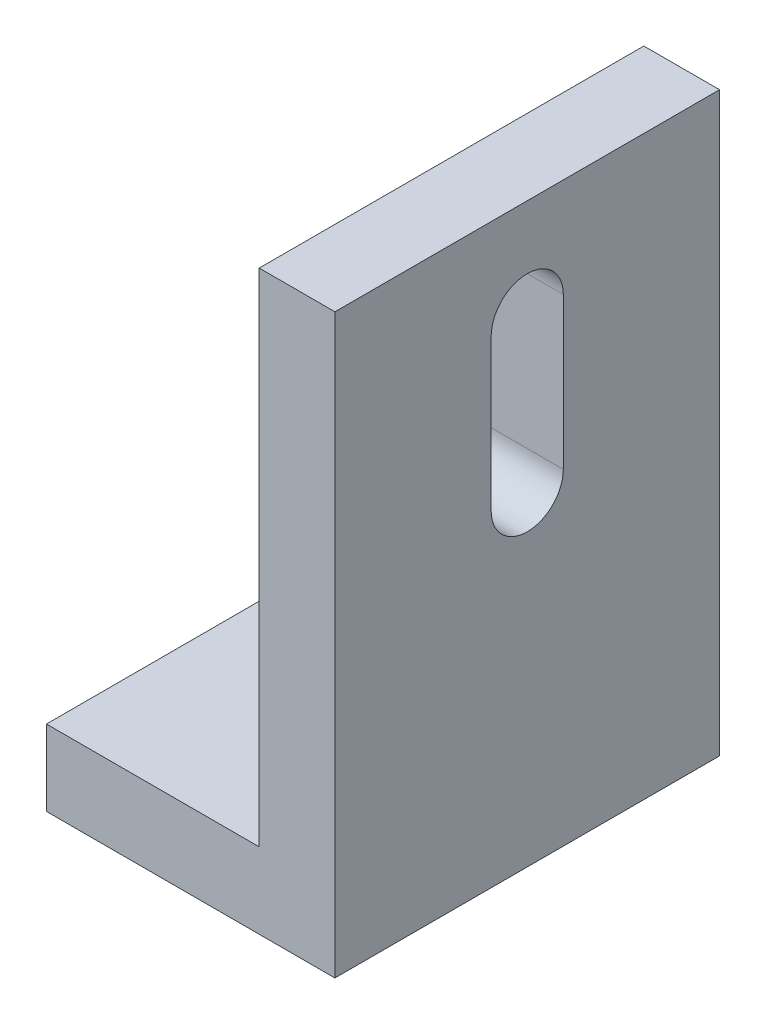
SolidWorks part; units mm, degrees
material "Aleación 6061"
ref_plane "Alzado" through (0, 0, 0) normal (0, 0, 1) x (1, 0, 0)
ref_plane "Planta" through (0, 0, 0) normal (0, 1, 0) x (1, 0, 0)
ref_plane "Vista lateral" through (0, 0, 0) normal (1, 0, 0) x (0, 0, -1)
sketch "Croquis1" plane through (0, 0, 0) normal (0, 0, 1) x (1, 0, 0)
  line L0 (0, 0) -> (38.1, 0)
  line L1 (38.1, 0) -> (38.1, 76.2)
  dimension "D1" = 76.2
  dimension "D2" = 38.1
extrude "Extruir-Lámina1" add sketch "Croquis1" along normal mid plane 50.8 thin thin type one direction reverse wall 10
sketch "Croquis2" plane through (0, 10, 0) normal (0, 1, 0) x (1, 0, 0)
  line L0 (14.05, 25.4) -> (14.05, -25.4) construction
  line L1 (0, 25.4) -> (28.1, 25.4) construction
  line L2 (0, -25.4) -> (28.1, -25.4) construction
  line L3 (0, 0) -> (28.1, 0) construction
  line L4 (28.1, -25.4) -> (28.1, 25.4) construction
  circle A0 centre (14.05, 0) radius 4.7625
  dimension "D1" = 9.525
extrude "Cortar-Extruir1" cut sketch "Croquis2" against normal through all
sketch "Croquis3" plane through (28.1, 0, 0) normal (-1, 0, 0) x (0, 0, 1)
  line L0 (0, 76.2) -> (0, 10) construction
  line L1 (25.4, 76.2) -> (-25.4, 76.2) construction
  line L2 (25.4, 10) -> (-25.4, 10) construction
  line L3 (0, 43.1) -> (0, 63.1) construction
  line L4 (-4.7625, 43.1) -> (-4.7625, 63.1)
  line L5 (4.7625, 43.1) -> (4.7625, 63.1)
  arc A0 (-4.7625, 43.1) -> (4.7625, 43.1) centre (0, 43.1) ccw
  arc A1 (4.7625, 63.1) -> (-4.7625, 63.1) centre (0, 63.1) ccw
  point P8 (0, 53.1)
  dimension "D1" = 9.525
  dimension "D2" = 20
extrude "Cortar-Extruir2" cut sketch "Croquis3" against normal up to vertex (10 mm away)
